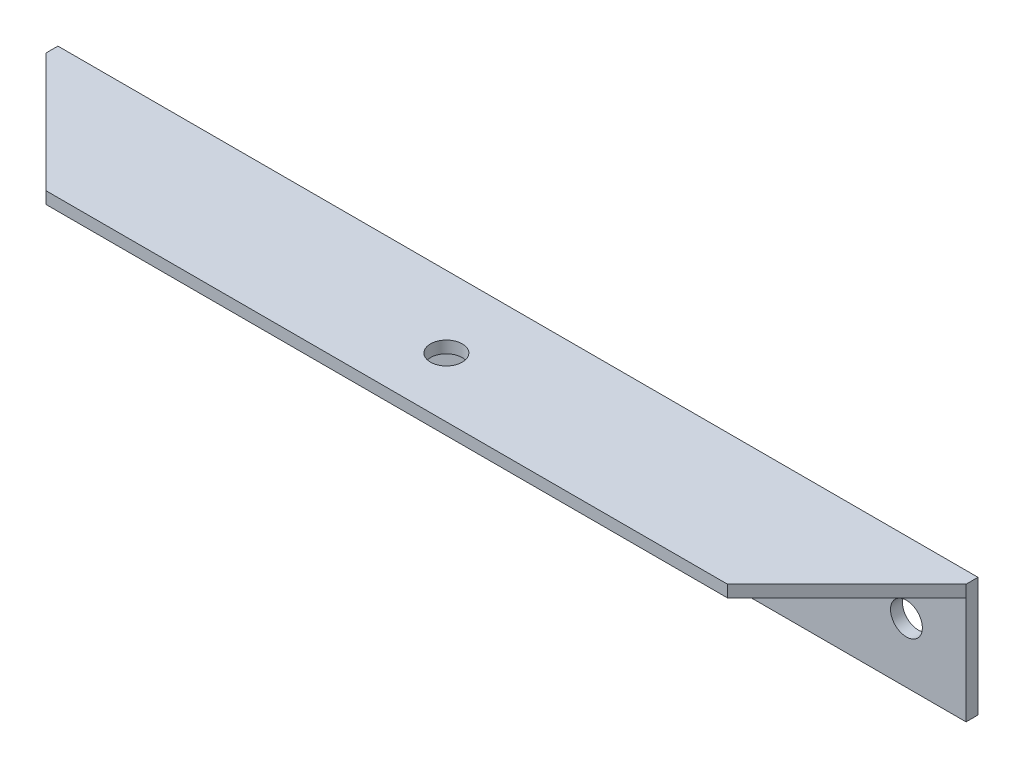
SolidWorks part; units mm, degrees
ref_plane "Front Plane" through (0, 0, 0) normal (0, 0, 1) x (1, 0, 0)
ref_plane "Top Plane" through (0, 0, 0) normal (0, 1, 0) x (1, 0, 0)
ref_plane "Right Plane" through (0, 0, 0) normal (1, 0, 0) x (0, 0, -1)
sketch "Sketch1" plane through (0, 0, 0) normal (0, 0, 1) x (1, 0, 0)
  line L0 (-115.7, 0) -> (115.7, 0)
  line L1 (115.7, 0) -> (115.7, -30)
  line L2 (115.7, -30) -> (-115.7, -30)
  line L3 (-115.7, -30) -> (-115.7, 0)
  point P4 (0, 0)
  dimension "D1" = 231.4
  dimension "D2" = 30
extrude "Boss-Extrude1" add sketch "Sketch1" along normal blind 3
sketch "Sketch2" plane through (0, 0, 0) normal (0, 1, 0) x (1, 0, 0)
  line L0 (115.7, -3) -> (-115.7, -3) construction
  line L1 (-115.7, -3) -> (115.7, -3)
  line L2 (-85.7, -33) -> (85.7, -33)
  line L3 (-115.7, -3) -> (-85.7, -33)
  line L4 (115.7, -3) -> (85.7, -33)
  dimension "D1" = 45
  dimension "D2" = 45
  dimension "D3" = 30
extrude "Boss-Extrude2" add sketch "Sketch2" against normal blind 3
sketch "Sketch10" plane through (0, 0, 0) normal (0, 1, 0) x (1, 0, 0)
  line L0 (-85.7, -33) -> (85.7, -33) construction
  line L1 (0, -33) -> (0, -18) construction
  dimension "D1" = 15
sketch "Sketch11" plane through (0, 0, 3) normal (0, 0, 1) x (1, 0, 0)
  line L0 (-115.7, -30) -> (-100.7, -30) construction
  line L1 (-115.7, -30) -> (115.7, -30) construction
  line L2 (-100.7, -30) -> (-100.7, -15) construction
  line L3 (115.7, -30) -> (100.7, -30) construction
  line L4 (100.7, -30) -> (100.7, -15) construction
  line L6 (115.7, -30) -> (62.5, -30) construction
  line L7 (62.5, -30) -> (62.5, -15) construction
  point P3 (-100.7, -15)
  point P4 (100.7, -15)
  point P15 (62.5, -15)
  dimension "D5" = 53.2
  dimension "D1" = 15
  dimension "D2" = 15
  dimension "D3" = 15
  dimension "D4" = 15
  dimension "D6" = 15
hole_wizard "Ø8.0 (8) Diameter Hole1" positions "Sketch12" profile "Sketch13" hole size "Ø8.0" standard "AS" end condition through all
sketch "Sketch12" plane through (0, 0, 3) normal (0, 0, 1) x (1, 0, 0)
  point P0 (-100.7, -15)
  point P3 (100.7, -15)
sketch "Sketch13" plane through (-100.7, -15, 3) normal (1, 0, 0) x (0, -1, 0)
  line L0 (0, 0) -> (0, 3)
  line L1 (0, 3) -> (4, 3)
  line L2 (4, 3) -> (4, 0)
  line L5 (4, 0) -> (0, 0)
  line L11 (0, -6.35) -> (0, 107.95) construction
  dimension "Thru Hole Dia." = 8
  dimension "Thru Hole Depth" = 3
hole_wizard "Ø8.0 (8) Diameter Hole2" positions "Sketch17" profile "Sketch18" hole size "Ø8.0" standard "AS" end condition through all
sketch "Sketch17" plane through (0, 0, 0) normal (0, 1, 0) x (1, 0, 0)
  point P0 (0, -18)
sketch "Sketch18" plane through (0, 0, 18) normal (1, 0, 0) x (0, 0, 1)
  line L0 (0, 0) -> (0, 30)
  line L1 (0, 30) -> (4, 30)
  line L2 (4, 30) -> (4, 0)
  line L5 (4, 0) -> (0, 0)
  line L11 (0, -6.35) -> (0, 107.95) construction
  dimension "Thru Hole Dia." = 8
  dimension "Thru Hole Depth" = 30
hole_wizard "Ø10.0 (10) Diameter Hole1" positions "Sketch24" profile "Sketch25" hole size "Ø10.0" standard "AS" end condition through all
sketch "Sketch24" plane through (0, 0, 3) normal (0, 0, 1) x (1, 0, 0)
  point P0 (62.5, -15)
sketch "Sketch25" plane through (62.5, -15, 3) normal (1, 0, 0) x (0, -1, 0)
  line L0 (0, 0) -> (0, 3)
  line L1 (0, 3) -> (5, 3)
  line L2 (5, 3) -> (5, 0)
  line L5 (5, 0) -> (0, 0)
  line L11 (0, -6.35) -> (0, 107.95) construction
  dimension "Thru Hole Dia." = 10
  dimension "Thru Hole Depth" = 3
